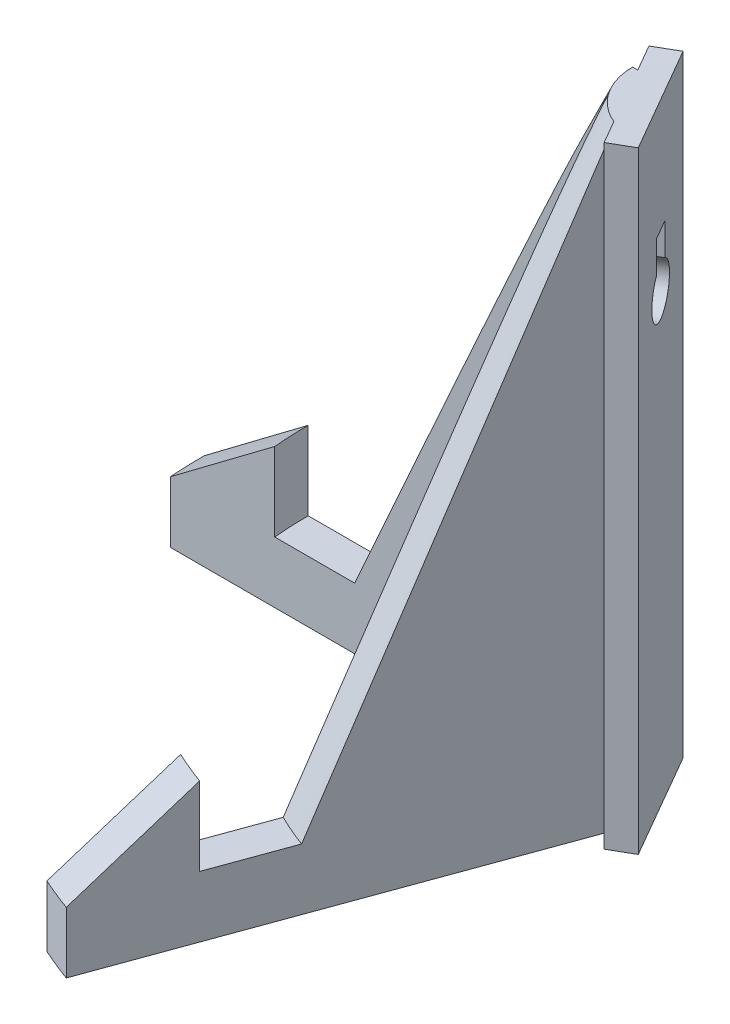
SolidWorks part; units mm, degrees
ref_plane "Front Plane" through (0, 0, 0) normal (0, 0, 1) x (1, 0, 0)
ref_plane "Top Plane" through (0, 0, 0) normal (0, 1, 0) x (1, 0, 0)
ref_plane "Right Plane" through (0, 0, 0) normal (1, 0, 0) x (0, 0, -1)
sketch "Sketch3" plane through (0, 0, 0) normal (0, 0, 1) x (1, 0, 0)
  line L0 (0, 0) -> (80, 0)
  line L1 (80, 0) -> (80, 100)
  line L7 (0, 10) -> (0, 0)
  line L8 (80, 100) -> (70, 100)
  line L11 (30, 10) -> (70, 100)
  line L12 (30, 10) -> (17, 10)
  line L13 (17, 10) -> (17, 22.8096)
  line L14 (17, 22.8096) -> (0, 10)
  dimension "D1" = 100
  dimension "D2" = 80
  dimension "D3" = 98.4886
  dimension "D4" = 13
  dimension "D5" = 21.2858
  dimension "D6" = 10
  dimension "D7" = 10
revolve "Revolve1" add sketch "Sketch3" angle 70 about L1
sketch "Sketch5" plane through (0, 0, 0) normal (0, 1, 0) x (1, 0, 0)
  line L0 (8.5, 0) -> (8.5, -5.7358) construction
  line L1 (17, 0) -> (0, 0) construction
  line L2 (55.5456, -67.188) -> (47.3189, -73.0202) construction
  line L3 (58.4527, -59.2006) -> (52.6384, -75.1754) construction
  line L4 (0.2059, -5.7358) -> (71.8085, -5.7358)
  line L5 (71.8085, -5.7358) -> (47.3189, -73.0202)
  line L6 (0.2059, -5.7358) -> (2.2101, -73.0202)
  line L7 (2.2101, -73.0202) -> (47.3189, -73.0202)
  arc A0 (0, 0) -> (52.6384, -75.1754) centre (80, 0) ccw construction
  arc A1 (70, 0) -> (76.5798, -9.3969) centre (80, 0) ccw construction
  dimension "D1" = 71.6026
  dimension "D2" = 71.6026
extrude "Cut-Extrude1" cut sketch "Sketch5" against normal through all and the other way through all contours L7 L5 L4 L6
sketch "Sketch7" plane through (0, 100, 0) normal (0, 1, 0) x (1, 0, 0)
  line L15 (71.8085, -5.7358) -> (80, 0) construction
  line L16 (71.8902, 6.3609) -> (81.8902, -10.9596)
  line L17 (71.8902, 6.3609) -> (68.3538, 4.3191)
  line L18 (68.3538, 4.3191) -> (78.3538, -13.0014)
  line L19 (78.3538, -13.0014) -> (81.8902, -10.9596)
  point P6 (76.8902, -2.2994)
  point P9 (80, 0)
extrude "Boss-Extrude1" add sketch "Sketch7" against normal blind 100
sketch "Sketch8" plane through (0, 0, 0) normal (0, 1, 0) x (1, 0, 0)
  line L0 (71.8902, 6.3609) -> (81.8902, -10.9596)
  line L1 (81.8902, -10.9596) -> (87.1838, 1.252)
  line L2 (87.1838, 1.252) -> (71.8902, 6.3609)
extrude "Cut-Extrude2" cut sketch "Sketch8" against normal blind 100 and the other way blind 100 contours L2 L0 L1
sketch "Sketch9" plane through (56.672, 0, -32.7196) normal (0.866, 0, -0.5) x (-0.5, 0, -0.866)
  line L0 (-40.4364, 100) -> (-40.4364, 0) construction
  line L1 (-50.4364, 100) -> (-30.4364, 100) construction
  line L2 (-50.4364, 0) -> (-30.4364, 0) construction
  line L3 (-42.3762, 81.5758) -> (-38.4967, 81.5758)
  line L5 (-38.4967, 76.2899) -> (-38.4967, 81.5758)
  line L7 (-42.3762, 76.2899) -> (-42.3762, 81.5758)
  line L8 (-38.4967, 72.0265) -> (-42.3762, 81.5758) construction
  line L9 (-38.4967, 81.5758) -> (-42.3762, 72.0265) construction
  arc A0 (-42.3762, 76.2899) -> (-38.4967, 76.2899) centre (-40.4364, 72.8652) ccw
  point P8 (-40.4364, 76.8011)
extrude "Cut-Extrude4" cut sketch "Sketch9" against normal blind 100 contours L3 L5 A0 L7
